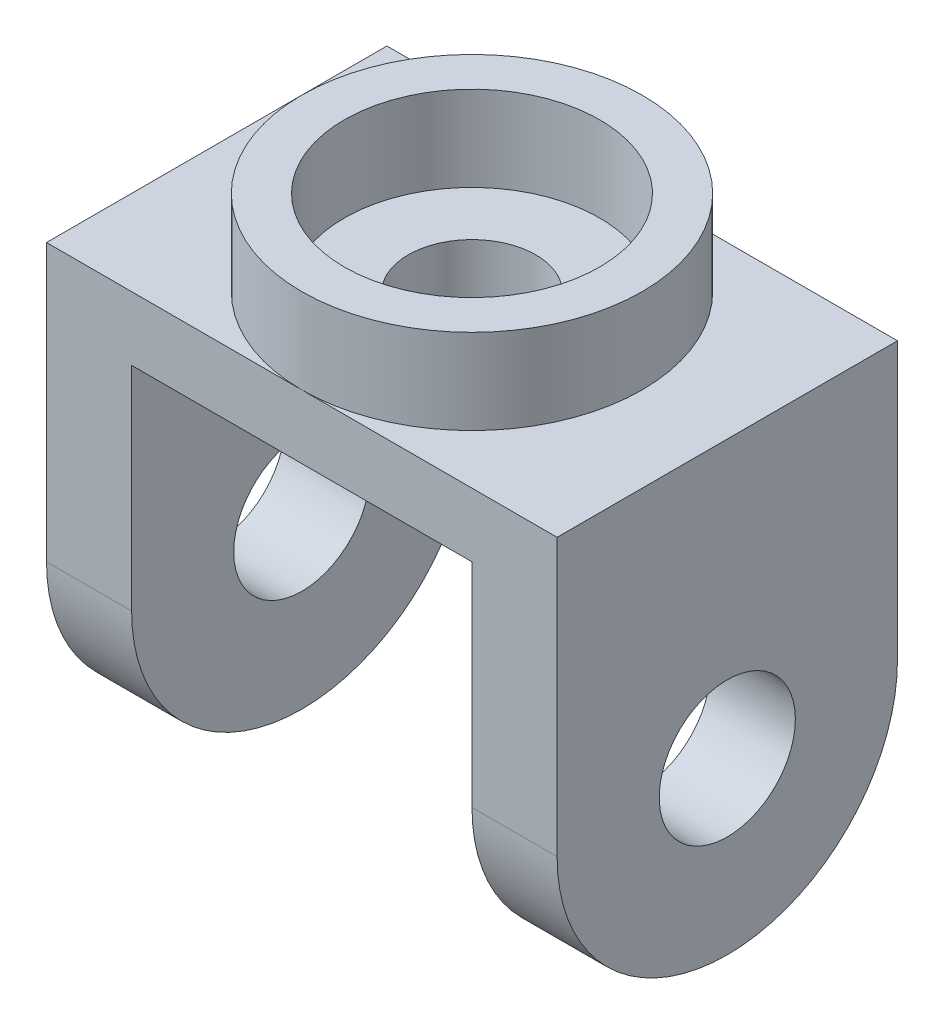
SolidWorks part; units mm, degrees
ref_plane "Front Plane" through (0, 0, 0) normal (0, 0, 1) x (1, 0, 0)
ref_plane "Top Plane" through (0, 0, 0) normal (0, 1, 0) x (1, 0, 0)
ref_plane "Right Plane" through (0, 0, 0) normal (1, 0, 0) x (0, 0, -1)
sketch "Sketch2" plane through (0, 0, 0) normal (0, 1, 0) x (1, 0, 0)
  line L1 (-60000, 40000) -> (60000, 40000)
  line L2 (-60000, 40000) -> (-60000, -40000)
  line L3 (-60000, -40000) -> (60000, -40000)
  line L4 (60000, 40000) -> (60000, -40000)
  line L5 (-60000, 40000) -> (60000, -40000) construction
  line L6 (-60000, -40000) -> (60000, 40000) construction
  point P0 (0, 0)
  dimension "D1" = 120000
  dimension "D2" = 80000
extrude "Boss-Extrude1" add sketch "Sketch2" along normal blind 15000
sketch "Sketch3" plane through (0, 15000, 0) normal (0, 1, 0) x (1, 0, 0)
  circle A0 centre (0, 0) radius 40000
  circle A1 centre (0, 0) radius 30000
extrude "Boss-Extrude2" add sketch "Sketch3" along normal blind 20000
sketch "Sketch4" plane through (0, 15000, 0) normal (0, 1, 0) x (1, 0, 0)
  circle A0 centre (0, 0) radius 15000
extrude "Cut-Extrude1" cut sketch "Sketch4" against normal blind 20000
sketch "Sketch7" plane through (-60000, 0, 0) normal (-1, 0, 0) x (0, 0, 1)
  line L2 (-40000, 0) -> (40000, 0)
  line L3 (-40000, 0) -> (-40000, -50000)
  line L4 (-40000, -50000) -> (40000, -50000)
  line L5 (40000, 0) -> (40000, -50000)
  arc A0 (40000, -50000) -> (-40000, -50000) centre (0, -50000) cw
  dimension "D2" = 40000
  dimension "D1" = 50000
extrude "Boss-Extrude4" add sketch "Sketch7" against normal blind 20000 contours L5 L2 L3 L4
sketch "Sketch9" plane through (-60000, 0, 0) normal (-1, 0, 0) x (0, 0, 1)
  line L0 (-40000, -50000) -> (40000, -50000) construction
  line L5 (-40000, 15000) -> (-40000, -50000)
  line L6 (-40000, -50000) -> (40000, -50000)
  line L7 (40000, -50000) -> (40000, 15000)
  line L8 (40000, 15000) -> (-40000, 15000)
  line L10 (-40000, -50000) -> (40000, -50000)
  arc A0 (40000, -50000) -> (-40000, -50000) centre (0, -50000) cw
  dimension "D1" = 0
extrude "Boss-Extrude5" add sketch "Sketch9" against normal blind 20000
sketch "Sketch11" plane through (-60000, 0, 0) normal (-1, 0, 0) x (0, 0, 1)
  circle A0 centre (0, -50000) radius 16000
extrude "Cut-Extrude3" cut sketch "Sketch11" against normal blind 20499.9604 contours A0
sketch "Sketch14" plane through (60000, 0, 0) normal (1, 0, 0) x (0, 0, -1)
  line L1 (-40000, 0) -> (40000, 0)
  line L2 (-40000, 0) -> (-40000, -50000)
  line L4 (40000, 0) -> (40000, -50000)
  arc A0 (-40000, -50000) -> (40000, -50000) centre (0, -50000) ccw
extrude "Boss-Extrude7" add sketch "Sketch14" against normal blind 20000
sketch "Sketch15" plane through (60000, 0, 0) normal (1, 0, 0) x (0, 0, -1)
  circle A0 centre (0, -50000) radius 16000
extrude "Cut-Extrude4" cut sketch "Sketch15" against normal blind 20000
